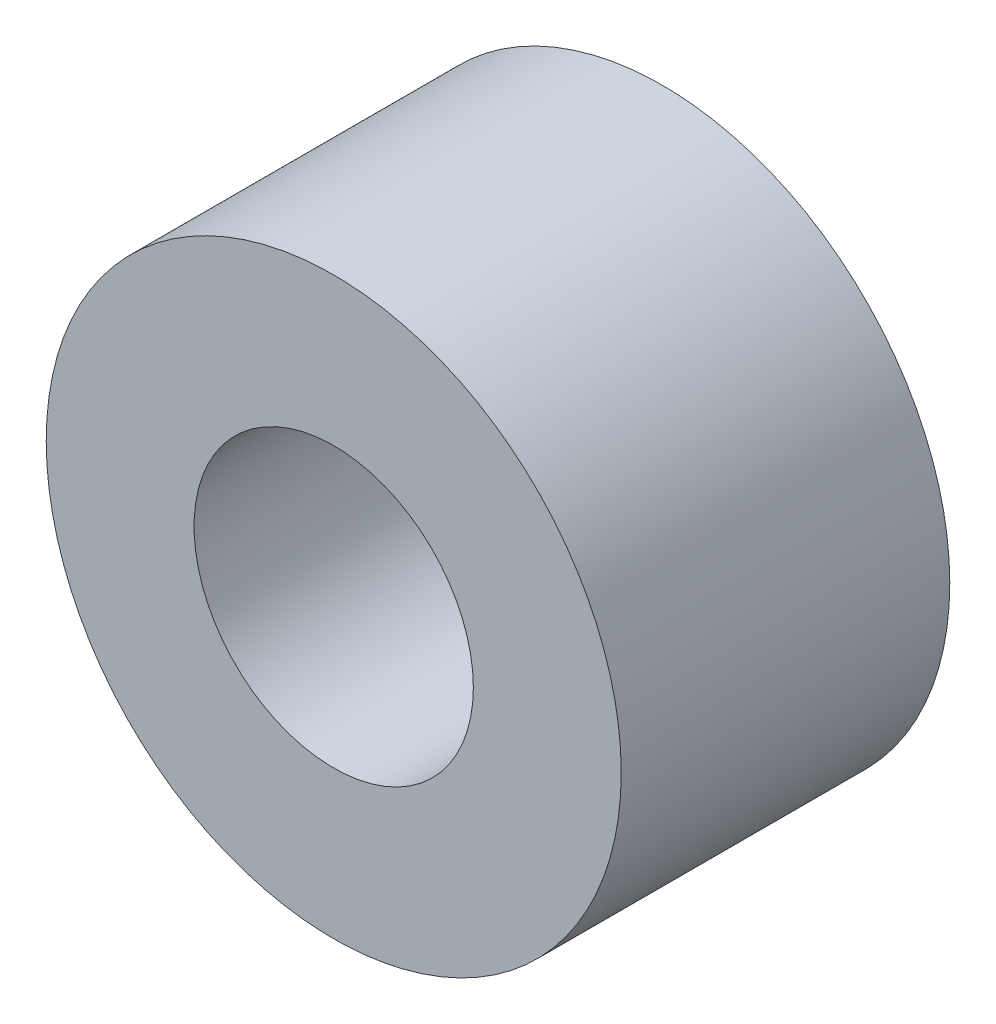
SolidWorks part; units mm, degrees
ref_plane "Front Plane" through (0, 0, 0) normal (0, 0, 1) x (1, 0, 0)
ref_plane "Top Plane" through (0, 0, 0) normal (0, 1, 0) x (1, 0, 0)
ref_plane "Right Plane" through (0, 0, 0) normal (1, 0, 0) x (0, 0, -1)
sketch "PCB insulation sleeve profile" plane through (0, 0, 0) normal (0, 0, 1) x (1, 0, 0)
  circle A0 centre (0, 0) radius 3.5
  circle A1 centre (0, 0) radius 1.7
extrude "PCB insulation sleeve" add sketch "PCB insulation sleeve profile" along normal blind 4
